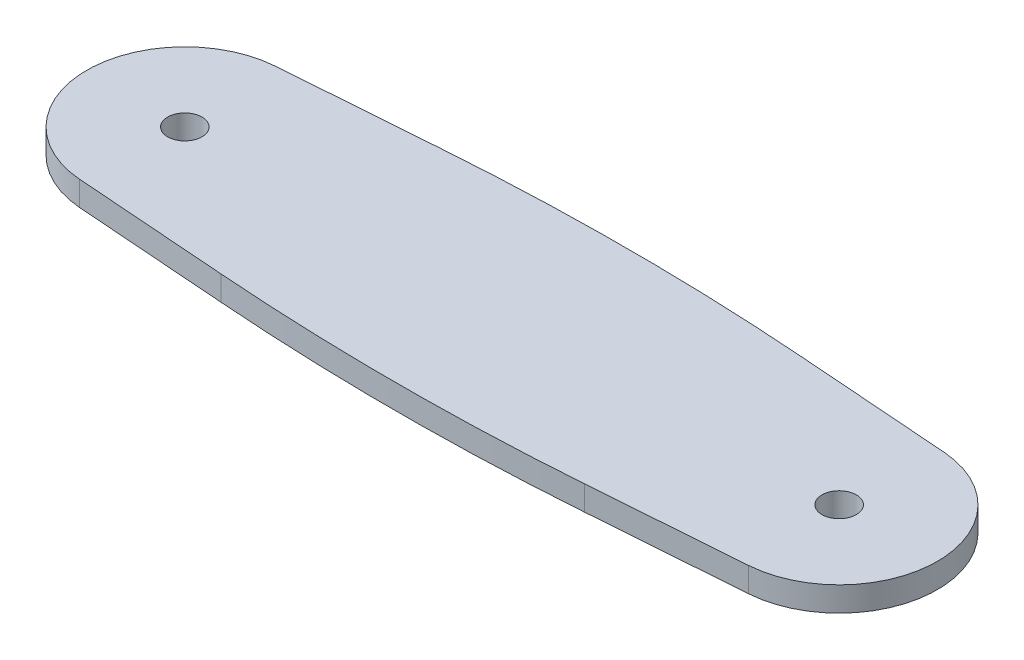
SolidWorks part; units mm, degrees
material "ABS"
ref_plane "前视基准面" through (0, 0, 0) normal (0, 0, 1) x (1, 0, 0)
ref_plane "上视基准面" through (0, 0, 0) normal (0, 1, 0) x (1, 0, 0)
ref_plane "右视基准面" through (0, 0, 0) normal (1, 0, 0) x (0, 0, -1)
other "Configuration Table"
sketch "草图1" plane through (0, 0, 0) normal (0, 1, 0) x (1, 0, 0)
  line L0 (0, 0) -> (80, 0) construction
  line L1 (-0.8877, 11.9671) -> (40, 15)
  line L2 (40, 15) -> (80.8877, 11.9671)
  line L3 (80.8877, -11.9671) -> (40, -15)
  line L4 (40, -15) -> (-0.8877, -11.9671)
  line L5 (40, 0) -> (40, -15) construction
  line L6 (40, 15) -> (40, 0) construction
  circle A0 centre (0, 0) radius 2.1
  circle A1 centre (80, 0) radius 2.1
  arc A3 (80.8877, 11.9671) -> (80.8877, -11.9671) centre (80, 0) cw
  arc A4 (-0.8877, 11.9671) -> (-0.8877, -11.9671) centre (0, 0) ccw
  dimension "D2" = 4.2
  dimension "D3" = 4.2
  dimension "D4" = 12
  dimension "D5" = 12
  dimension "D6" = 30
  dimension "D1" = 80
extrude "凸台-拉伸1" add sketch "草图1" along normal blind 3
fillet "圆角1" radius 300 2 edges at (40, 1.5, 15) (40, 1.5, -15)
